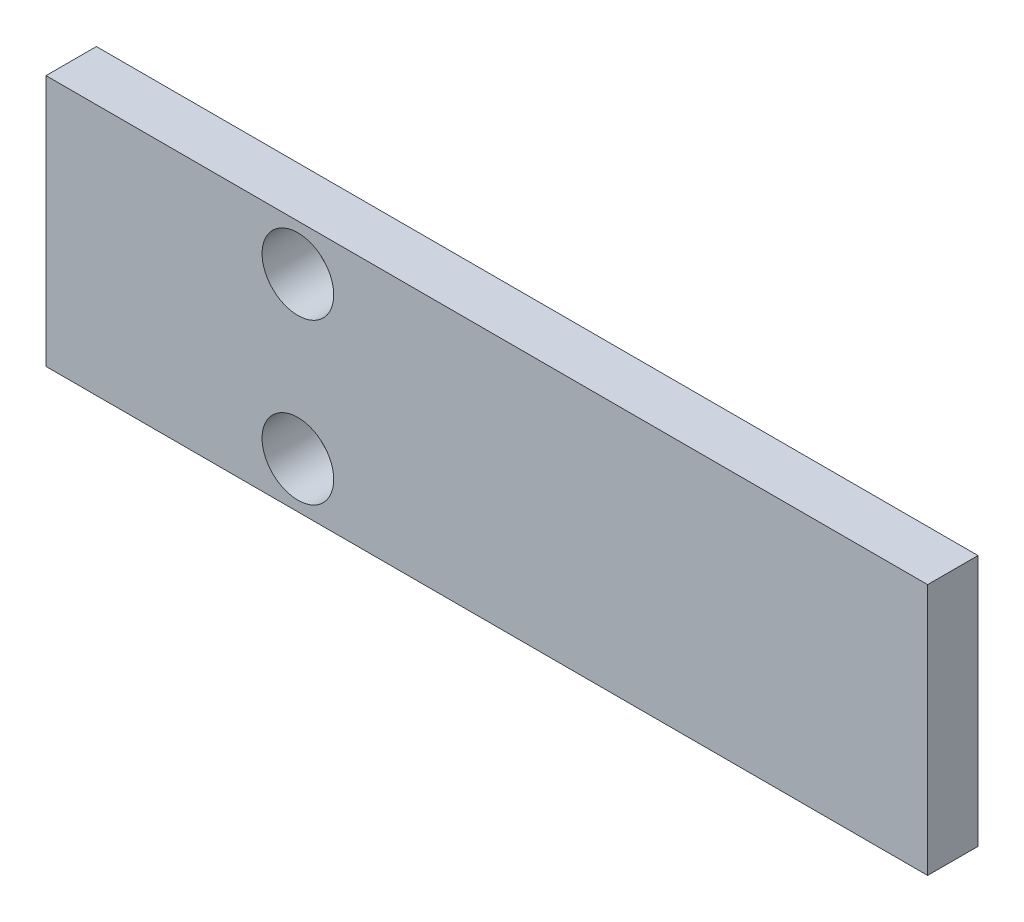
SolidWorks part; units mm, degrees
ref_plane "Front Plane" through (0, 0, 0) normal (0, 0, 1) x (1, 0, 0)
ref_plane "Top Plane" through (0, 0, 0) normal (0, 1, 0) x (1, 0, 0)
ref_plane "Right Plane" through (0, 0, 0) normal (1, 0, 0) x (0, 0, -1)
sketch "Sketch1" plane through (0, 0, 0) normal (0, 0, 1) x (1, 0, 0)
  line L1 (-17.5, -5) -> (17.5, -5)
  line L2 (-17.5, -5) -> (-17.5, 5)
  line L3 (-17.5, 5) -> (17.5, 5)
  line L4 (17.5, -5) -> (17.5, 5)
  line L5 (-17.5, -5) -> (17.5, 5) construction
  line L6 (-17.5, 5) -> (17.5, -5) construction
  point P0 (0, 0)
  dimension "D1" = 35
  dimension "D2" = 10
extrude "Boss-Extrude1" add sketch "Sketch1" along normal blind 2
sketch "Sketch2" plane through (0, 0, 2) normal (0, 0, 1) x (1, 0, 0)
  line L1 (-17.5, 5) -> (-17.5, -5) construction
  line L2 (-7.5, 3.175) -> (-7.5, -3.175) construction
  line L3 (-17.5, -0.3247) -> (-17.5, 0) construction
  line L4 (-17.5, 0) -> (17.5, 0) construction
  line L5 (17.5, -5) -> (17.5, 5) construction
  circle A0 centre (-7.5, 3.175) radius 1.4224
  circle A2 centre (-7.5, -3.175) radius 1.4224
  dimension "D1" = 2.8448
  dimension "D3" = 10
  dimension "D5" = 6.35
  dimension "D4" = 2
extrude "Cut-Extrude1" cut sketch "Sketch2" against normal up to next
